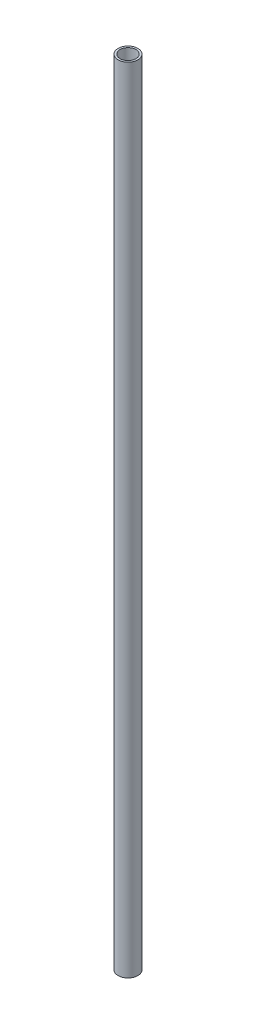
SolidWorks part; units mm, degrees
ref_plane "Front Plane" through (0, 0, 0) normal (0, 0, 1) x (1, 0, 0)
ref_plane "Top Plane" through (0, 0, 0) normal (0, 1, 0) x (1, 0, 0)
ref_plane "Right Plane" through (0, 0, 0) normal (1, 0, 0) x (0, 0, -1)
sketch "Sketch1" plane through (0, 0, 0) normal (0, 1, 0) x (1, 0, 0)
  circle A0 centre (0, 0) radius 12.5
  circle A1 centre (0, 0) radius 10
  dimension "D1" = 25
  dimension "D2" = 20
extrude "Boss-Extrude1" add sketch "Sketch1" along normal blind 1000
